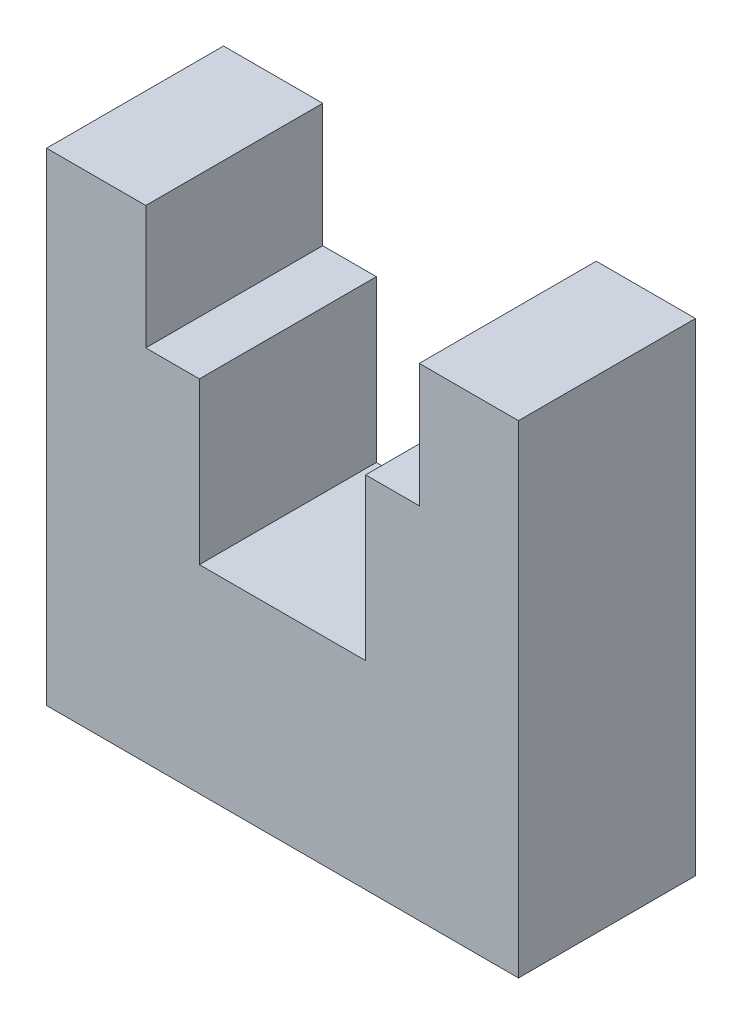
SolidWorks part; units mm, degrees
ref_plane "Front Plane" through (0, 0, 0) normal (0, 0, 1) x (1, 0, 0)
ref_plane "Top Plane" through (0, 0, 0) normal (0, 1, 0) x (1, 0, 0)
ref_plane "Right Plane" through (0, 0, 0) normal (1, 0, 0) x (0, 0, -1)
sketch "Sketch1" plane through (0, 0, 0) normal (0, 0, 1) x (1, 0, 0)
  line L0 (0, 6.6003) -> (0, 0) construction
  line L1 (-2.55, 9) -> (-4.4, 9)
  line L2 (-4.4, 9) -> (-4.4, 0)
  line L3 (-4.4, 0) -> (4.4, 0)
  line L4 (-2.55, 6.7) -> (-1.55, 6.7)
  line L5 (-1.55, 6.7) -> (-1.55, 3.7)
  line L6 (-2.55, 9) -> (-2.55, 6.7)
  line L7 (-1.55, 3.7) -> (1.55, 3.7)
  line L8 (0, 3.7) -> (0, 0)
  line L9 (2.55, 9) -> (2.55, 6.7)
  line L10 (1.55, 6.7) -> (1.55, 3.7)
  line L11 (2.55, 6.7) -> (1.55, 6.7)
  line L12 (4.4, 9) -> (4.4, 0)
  line L13 (2.55, 9) -> (4.4, 9)
  dimension "D1" = 1.55
  dimension "D2" = 2.55
  dimension "D3" = 4.4
  dimension "D4" = 2.3
  dimension "D5" = 3
  dimension "D6" = 9
extrude "Boss-Extrude1" add sketch "Sketch1" along normal blind 3.3 contours L8 L7 L5 L4 L6 L1 L2 L3 | L13 L9 L11 L10 L7 L8 L3 L12
